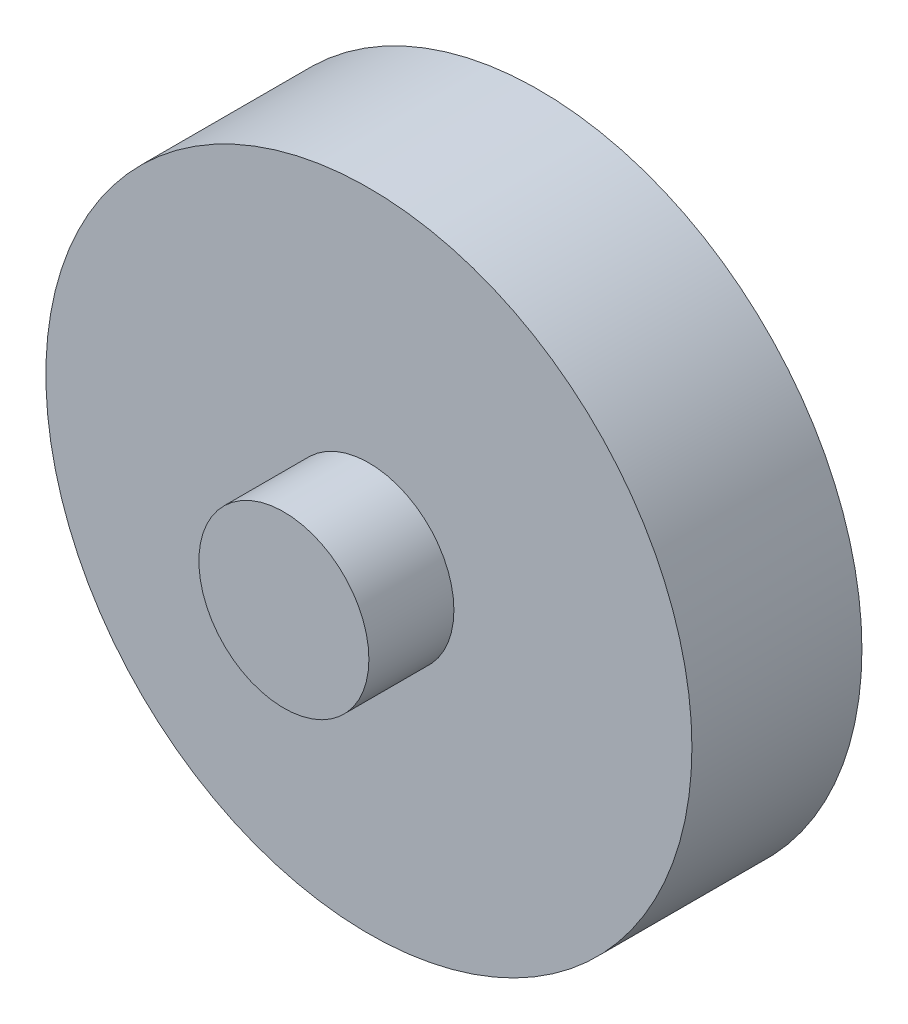
SolidWorks part; units mm, degrees
ref_plane "Front Plane" through (0, 0, 0) normal (0, 0, 1) x (1, 0, 0)
ref_plane "Top Plane" through (0, 0, 0) normal (0, 1, 0) x (1, 0, 0)
ref_plane "Right Plane" through (0, 0, 0) normal (1, 0, 0) x (0, 0, -1)
sketch "Sketch1" plane through (0, 0, 0) normal (0, 0, 1) x (1, 0, 0)
  circle A0 centre (0, 0) radius 48.26
extrude "Boss-Extrude1" add sketch "Sketch1" along normal blind 25.4
sketch "Sketch2" plane through (0, 0, 25.4) normal (0, 0, 1) x (1, 0, 0)
  circle A0 centre (0, 0) radius 12.7
extrude "Boss-Extrude2" add sketch "Sketch2" along normal blind 12.7
sketch "Sketch3" plane through (0, 0, 0) normal (0, 0, -1) x (-1, 0, 0)
  circle A0 centre (0, 0) radius 12.7
extrude "Boss-Extrude3" add sketch "Sketch3" along normal blind 12.7
